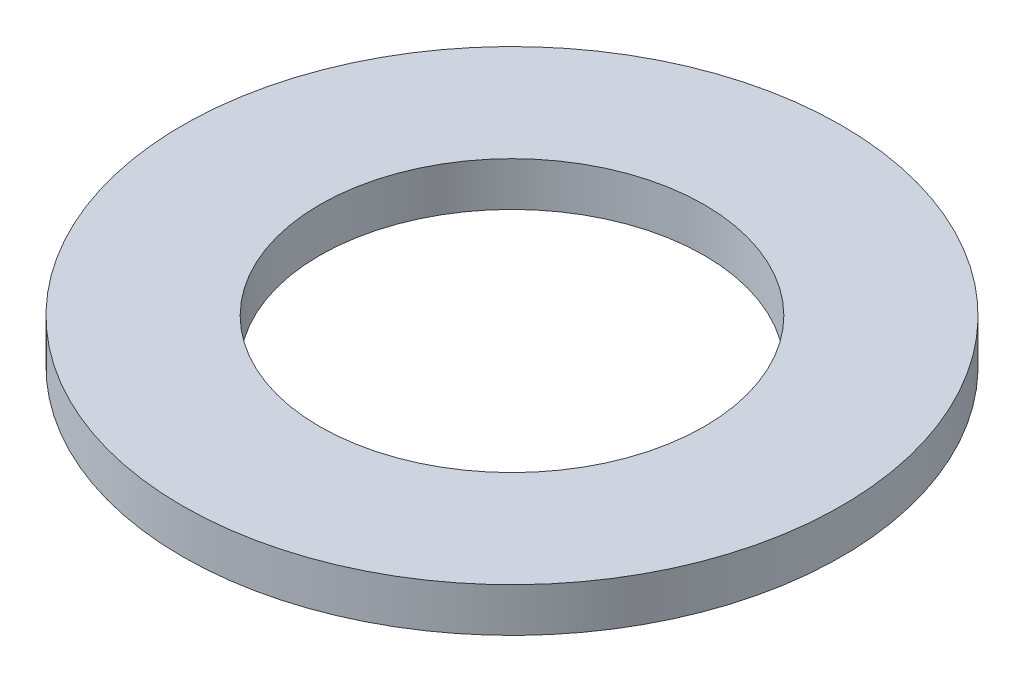
SolidWorks part; units mm, degrees
ref_plane "Front Plane" through (0, 0, 0) normal (0, 0, 1) x (1, 0, 0)
ref_plane "Top Plane" through (0, 0, 0) normal (0, 1, 0) x (1, 0, 0)
ref_plane "Right Plane" through (0, 0, 0) normal (1, 0, 0) x (0, 0, -1)
sketch "Sketch1" plane through (0, 0, 0) normal (0, 1, 0) x (1, 0, 0)
  circle A0 centre (0, 0) radius 1.75
  circle A1 centre (0, 0) radius 3
  dimension "D1" = 3.5
  dimension "D2" = 6
extrude "Boss-Extrude1" add sketch "Sketch1" along normal blind 0.4
